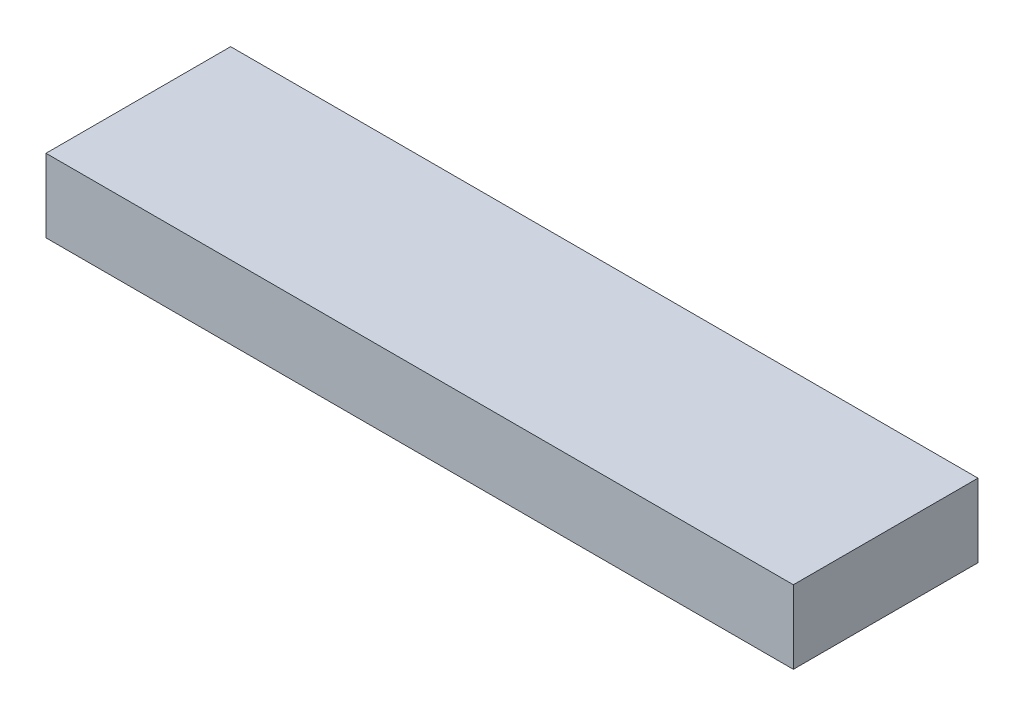
SolidWorks part; units mm, degrees
ref_plane "Front Plane" through (0, 0, 0) normal (0, 0, 1) x (1, 0, 0)
ref_plane "Top Plane" through (0, 0, 0) normal (0, 1, 0) x (1, 0, 0)
ref_plane "Right Plane" through (0, 0, 0) normal (1, 0, 0) x (0, 0, -1)
sketch "Sketch1" plane through (0, 0, 0) normal (0, 1, 0) x (1, 0, 0)
  line L1 (-64.77, -16.002) -> (64.77, -16.002)
  line L2 (-64.77, -16.002) -> (-64.77, 16.002)
  line L3 (-64.77, 16.002) -> (64.77, 16.002)
  line L4 (64.77, -16.002) -> (64.77, 16.002)
  line L5 (-64.77, -16.002) -> (64.77, 16.002) construction
  line L6 (-64.77, 16.002) -> (64.77, -16.002) construction
  point P0 (0, 0)
  dimension "D1" = 32.004
  dimension "D2" = 129.54
extrude "Boss-Extrude1" add sketch "Sketch1" along normal blind 12.7
